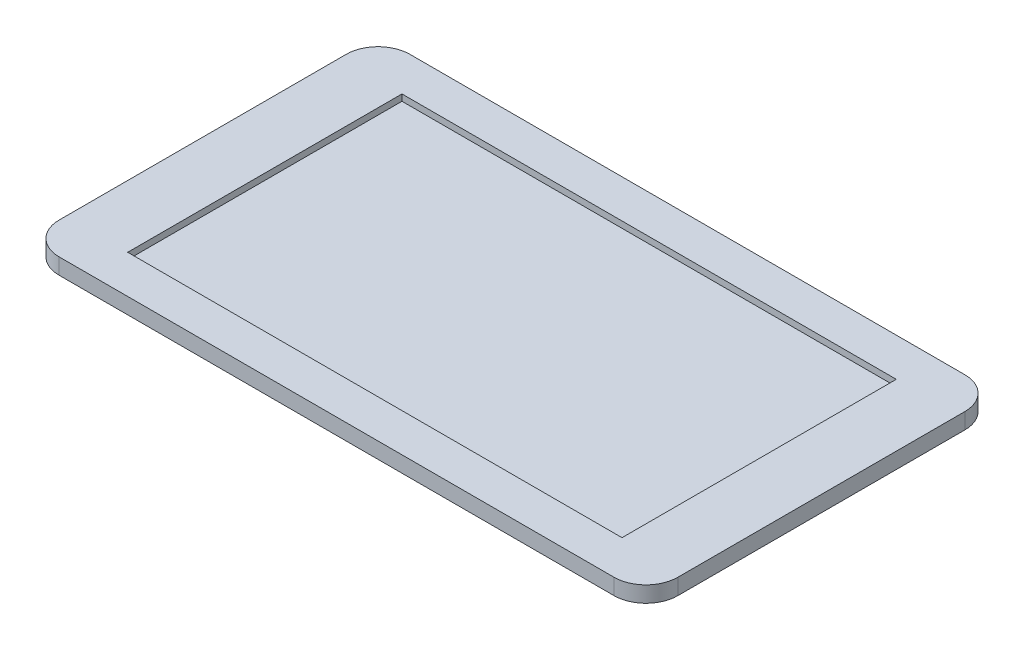
SolidWorks part; units mm, degrees
ref_plane "Front Plane" through (0, 0, 0) normal (0, 0, 1) x (1, 0, 0)
ref_plane "Top Plane" through (0, 0, 0) normal (0, 1, 0) x (1, 0, 0)
ref_plane "Right Plane" through (0, 0, 0) normal (1, 0, 0) x (0, 0, -1)
sketch "Sketch1" plane through (0, 0, 0) normal (0, 1, 0) x (1, 0, 0)
  line L1 (-97, -55) -> (97, -55)
  line L2 (-97, -55) -> (-97, 55)
  line L3 (-97, 55) -> (97, 55)
  line L4 (97, -55) -> (97, 55)
  line L5 (-97, -55) -> (97, 55) construction
  line L6 (-97, 55) -> (97, -55) construction
  point P0 (0, 0)
  dimension "D1" = 194
  dimension "D2" = 110
extrude "Boss-Extrude1" add sketch "Sketch1" against normal blind 5
fillet "Fillet1" radius 10 4 edges at (97, -2.5, 55) (97, -2.5, -55) (-97, -2.5, -55) (-97, -2.5, 55)
sketch "Sketch2" plane through (0, 0, 0) normal (0, 1, 0) x (1, 0, 0)
  line L1 (-77.5, -43) -> (77.5, -43)
  line L2 (-77.5, -43) -> (-77.5, 43)
  line L3 (-77.5, 43) -> (77.5, 43)
  line L4 (77.5, -43) -> (77.5, 43)
  line L5 (-77.5, -43) -> (77.5, 43) construction
  line L6 (-77.5, 43) -> (77.5, -43) construction
  point P0 (0, 0)
  dimension "D1" = 155
  dimension "D2" = 86
extrude "Cut-Extrude1" cut sketch "Sketch2" against normal blind 2
sketch "Sketch3" plane through (0, -5, 0) normal (0, -1, 0) x (1, 0, 0)
  line L1 (-29, -24.5) -> (29, -24.5) construction
  line L2 (-29, -24.5) -> (-29, 24.5) construction
  line L3 (-29, 24.5) -> (29, 24.5) construction
  line L4 (29, -24.5) -> (29, 24.5) construction
  line L5 (-29, -24.5) -> (29, 24.5) construction
  line L6 (-29, 24.5) -> (29, -24.5) construction
  line L7 (-33.875, -29.375) -> (33.875, -29.375)
  line L8 (-33.875, -29.375) -> (-33.875, 29.375)
  line L9 (-33.875, 29.375) -> (33.875, 29.375)
  line L10 (33.875, -29.375) -> (33.875, 29.375)
  line L11 (-33.875, -29.375) -> (33.875, 29.375) construction
  line L12 (-33.875, 29.375) -> (33.875, -29.375) construction
  circle A0 centre (-29, 24.5) radius 1.375
  circle A1 centre (29, 24.5) radius 1.375
  circle A2 centre (29, -24.5) radius 1.375
  circle A3 centre (-29, -24.5) radius 1.375
  point P0 (0, 0)
  point P10 (0, 0)
  point P15 (29, -25.875)
  point P16 (30.375, -24.5)
  dimension "D3" = 2.75
  dimension "D1" = 58
  dimension "D2" = 49
  dimension "D4" = 3.5
  dimension "D5" = 3.5
extrude "Boss-Extrude2" add sketch "Sketch3" along normal blind 5
